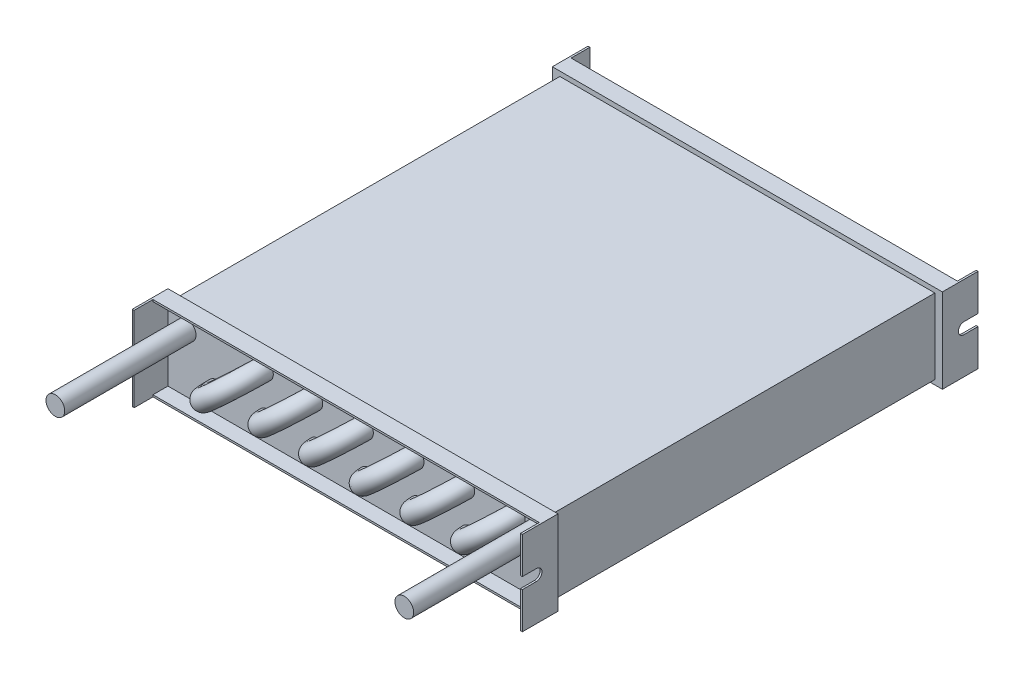
SolidWorks part; units mm, degrees
ref_plane "Front Plane" through (0, 0, 0) normal (0, 0, 1) x (1, 0, 0)
ref_plane "Top Plane" through (0, 0, 0) normal (0, 1, 0) x (1, 0, 0)
ref_plane "Right Plane" through (0, 0, 0) normal (1, 0, 0) x (0, 0, -1)
sketch "Sketch1" plane through (0, 0, 0) normal (0, 0, 1) x (1, 0, 0)
  line L1 (-104, -22.5) -> (104, -22.5)
  line L2 (-104, -22.5) -> (-104, 22.5)
  line L3 (-104, 22.5) -> (104, 22.5)
  line L4 (104, -22.5) -> (104, 22.5)
  line L5 (-104, -22.5) -> (104, 22.5) construction
  line L6 (-104, 22.5) -> (104, -22.5) construction
  point P0 (0, 0)
  dimension "D1" = 208
  dimension "D2" = 45
extrude "Boss-Extrude1" add sketch "Sketch1" along normal blind 9
shell "Shell1" thickness 1
sketch "Sketch2" plane through (0, 0, 0) normal (0, 0, -1) x (-1, 0, 0)
  line L1 (-100, 20) -> (100, 20)
  line L2 (-100, 20) -> (-100, -20)
  line L3 (-100, -20) -> (100, -20)
  line L4 (100, 20) -> (100, -20)
  line L5 (-100, 20) -> (100, -20) construction
  line L6 (-100, -20) -> (100, 20) construction
  point P0 (0, 0)
  dimension "D1" = 200
  dimension "D2" = 40
extrude "Boss-Extrude2" add sketch "Sketch2" along normal blind 205
sketch "Sketch3" plane through (0, 20, 0) normal (0, 1, 0) x (1, 0, 0)
  line L0 (0, 102.5) -> (8.4626, 110.9626)
ref_plane "Plane1" through (0, 0, -102.5) normal (0, 0, 1) x (1, 0, 0)
mirror "Mirror4" about plane through (0, 0, -102.5) normal (0, 0, 1) of "Boss-Extrude1"
sketch "Sketch4" plane through (0, 0, 1) normal (0, 0, 1) x (1, 0, 0)
  circle A0 centre (-93.0351, 9.4654) radius 5
  dimension "D1" = 10
extrude "Boss-Extrude3" add sketch "Sketch4" along normal blind 70
sketch "Sketch9" plane through (104, 0, 0) normal (1, 0, 0) x (0, 0, -1)
  line L0 (0, 22.5) -> (-19, 22.5)
  line L1 (-19, 22.5) -> (-19, -22.5)
  line L2 (-19, -22.5) -> (0, -22.5)
  line L7 (0, -22.5) -> (0, 22.5)
  line L8 (0, 22.5) -> (-9, 22.5)
  line L9 (-9, 22.5) -> (-9, -22.5)
  line L10 (-9, -22.5) -> (0, -22.5)
  line L12 (0, 22.5) -> (-9, 22.5)
  line L13 (-9, 22.5) -> (-9, -22.5)
  line L14 (-9, -22.5) -> (0, -22.5)
  line M7 (-9, 22.5) -> (-9, -22.5)
  dimension "D1" = 19
  dimension "D2" = 0
extrude "Boss-Extrude7" add sketch "Sketch9" against normal blind 1 contours L1 L2 L0 M7
sketch "Sketch11" plane through (104, 0, 0) normal (1, 0, 0) x (0, 0, -1)
  line L0 (-11.529, 3) -> (-19, 3)
  line L1 (-19, 22.5) -> (-19, -22.5) construction
  line L2 (-11.529, -3) -> (-19, -3)
  arc A0 (-11.529, -3) -> (-11.529, 3) centre (-11.529, 0) ccw
  line M3 (-19, 22.5) -> (-19, -22.5)
  dimension "D1" = 6
extrude "Cut-Extrude2" cut sketch "Sketch11" against normal blind 4 contours L2 A0 L0 M3
sketch "Sketch15" plane through (-104, 0, 0) normal (-1, 0, 0) x (0, 0, 1)
  line L0 (9, 22.5) -> (19, 22.5)
  line L1 (19, 22.5) -> (19, 3)
  line L2 (19, 22.5) -> (19, 3) construction
  line L3 (19, 3) -> (19, -22.5)
  line L4 (19, -22.5) -> (9, -22.5)
  line L5 (9, -22.5) -> (9, 22.5)
extrude "Boss-Extrude8" add sketch "Sketch15" against normal blind 1
ref_plane "Plane7" through (0, 0, -102.5) normal (0, 0, 1) x (1, 0, 0)
mirror "Mirror8" about plane through (0, 0, -102.5) normal (0, 0, 1) of "Boss-Extrude1"
mirror "Mirror9" about plane through (0, 0, -102.5) normal (0, 0, 1) of "Boss-Extrude1"
sketch "Sketch20" plane through (0, 0, -214) normal (0, 0, -1) x (-1, 0, 0)
  line L1 (-103, -21.5) -> (103, -21.5)
  line L2 (-103, -21.5) -> (-103, 21.5)
  line L3 (-103, 21.5) -> (103, 21.5)
  line L4 (103, -21.5) -> (103, 21.5)
  line L5 (-103, -21.5) -> (103, 21.5) construction
  line L6 (-103, 21.5) -> (103, -21.5) construction
  point P0 (0, 0)
  dimension "D1" = 206
  dimension "D2" = 43
extrude "Cut-Extrude4" cut sketch "Sketch20" against normal blind 8
mirror "Mirror12" about plane through (0, 0, -102.5) normal (0, 0, 1) of "Cut-Extrude2", "Boss-Extrude7"
mirror "Mirror13" about plane through (0, 0, 0) normal (1, 0, 0) of "Boss-Extrude3"
mirror "Mirror14" about plane through (0, 0, 0) normal (1, 0, 0) of "Cut-Extrude2"
mirror "Mirror17" about plane through (0, 0, -102.5) normal (0, 0, 1) of "Mirror14"
mirror "Mirror19" about plane through (0, 0, -102.5) normal (0, 0, 1) of "Boss-Extrude8"
mirror "Mirror20" about plane through (0, 0, -102.5) normal (0, 0, 1) of "Mirror14"
sketch "Sketch25" plane through (-100, 0, 0) normal (-1, 0, 0) x (0, 0, 1)
  line L0 (-11.1303, 13.0245) -> (-35.879, -11.7243)
  dimension "D1" = 35
sketch "Sketch26" plane through (0, 0, 1) normal (0, 0, 1) x (1, 0, 0)
  line L0 (-42.8968, 11.7477) -> (-77.8968, -11.4675)
  dimension "D1" = 35
sketch "Sketch27" plane through (0, 20, 0) normal (0, 1, 0) x (1, 0, 0)
  line L0 (-42.8968, -1) -> (-42.8968, 214)
  line L1 (-42.8968, -1) -> (-77.8968, -1) construction
  line L2 (103, 214) -> (-103, 214) construction
ref_plane "Plane8" through (-29.1187, 32.3875, 0) normal (-0.6686, 0.7436, 0) x (0.7436, 0.6686, 0)
sketch "Sketch28" plane through (-29.1187, 32.3875, 0) normal (-0.6686, 0.7436, 0) x (0.7436, 0.6686, 0)
  line L0 (-65.516, 5.536) -> (-65.516, 203.4455)
  line L2 (-30.516, 203.4455) -> (-30.516, 5.536)
  arc A0 (-30.516, 203.4455) -> (-65.516, 203.4455) centre (-48.016, 203.4455) ccw
  arc A1 (-65.516, 5.536) -> (-30.516, 5.536) centre (-48.016, 5.536) ccw
  dimension "D3" = 35
  dimension "D4" = 35
sketch "Sketch32" plane through (0, 0, -206) normal (0, 0, -1) x (-1, 0, 0)
  line L0 (77.8388, -11.4154) -> (51.8115, 11.9851) construction
  circle A0 centre (51.8115, 11.9851) radius 5
  dimension "D1" = 10
sweep "Sweep1" add profiles "Sketch32" path "Sketch28"
mirror "Mirror21" about plane through (0, 0, -102.5) normal (0, 0, 1) of "Sweep1"
pattern_linear "LPattern1" count 6 spacing 27 along (1, 0, 0) of "Sweep1"
